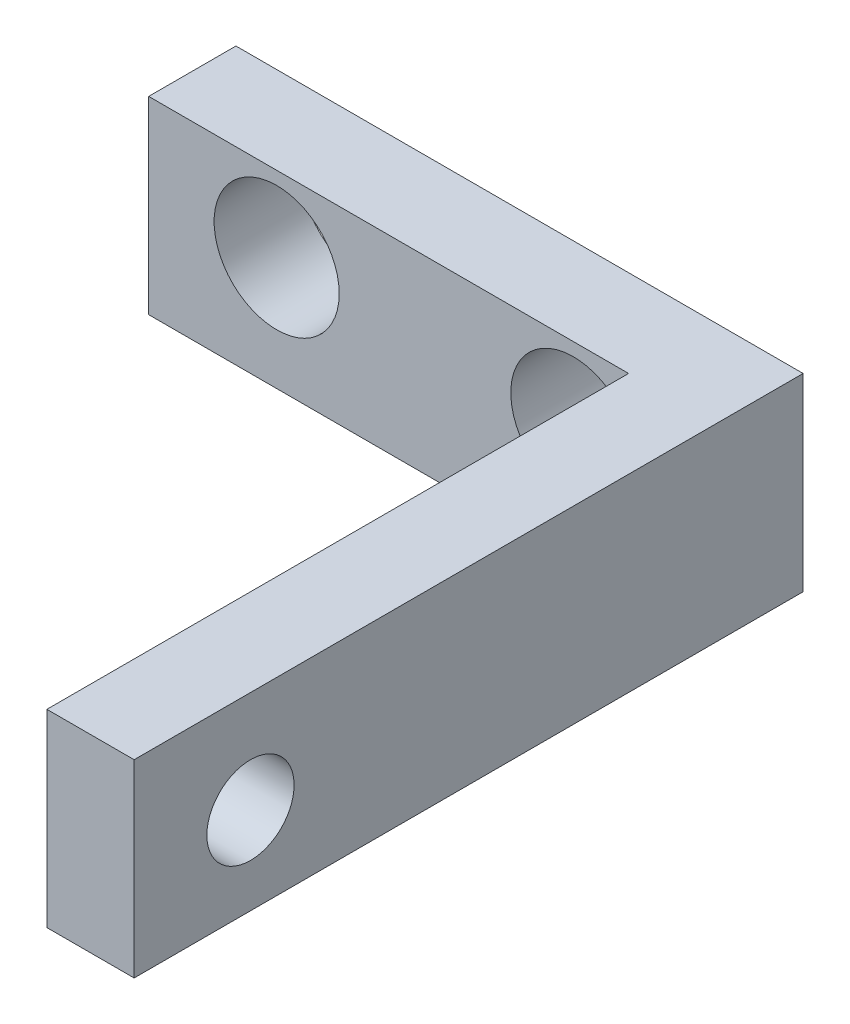
SolidWorks part; units mm, degrees
ref_plane "Front Plane" through (0, 0, 0) normal (0, 0, 1) x (1, 0, 0)
ref_plane "Top Plane" through (0, 0, 0) normal (0, 1, 0) x (1, 0, 0)
ref_plane "Right Plane" through (0, 0, 0) normal (1, 0, 0) x (0, 0, -1)
sketch "Sketch1" plane through (0, 0, 0) normal (0, 0, 1) x (1, 0, 0)
  line L0 (14.3846, -19.5704) -> (14.3846, -24.9359) construction
  line L1 (14.3846, -17.7588) -> (33.8846, -17.7588)
  line L2 (14.3846, -17.7588) -> (14.3846, -24.2588)
  line L3 (14.3846, -24.2588) -> (33.8846, -24.2588)
  line L4 (33.8846, -17.7588) -> (33.8846, -24.2588)
  line L5 (27.6846, -17.7588) -> (20.0846, -17.7588) construction
  line L11 (33.8846, -0.7588) -> (33.8846, 91.2412) construction
extrude "Boss-Extrude1" add sketch "Sketch1" along normal blind 3
sketch "Sketch2" plane through (0, 0, 3) normal (0, 0, 1) x (1, 0, 0)
  line L0 (14.3846, -24.2588) -> (33.8846, -24.2588) construction
  line L1 (33.8846, -17.7588) -> (30.8846, -17.7588)
  line L2 (33.8846, -17.7588) -> (33.8846, -24.2588)
  line L3 (33.8846, -24.2588) -> (30.8846, -24.2588)
  line L4 (30.8846, -17.7588) -> (30.8846, -24.2588)
  dimension "D1" = 3
extrude "Boss-Extrude2" add sketch "Sketch2" along normal blind 20
sketch "Sketch3" plane through (30.8846, 0, 0) normal (-1, 0, 0) x (0, 0, 1)
  line L0 (23, -17.7588) -> (23, -24.2588) construction
  line L1 (23, -17.7588) -> (3, -17.7588) construction
  circle A0 centre (19, -21.2588) radius 1.5
  dimension "D1" = 3
  dimension "D3" = 4
  dimension "D4" = 3.5
extrude "Cut-Extrude1" cut sketch "Sketch3" against normal blind 10
sketch "Sketch4" plane through (0, 0, 3) normal (0, 0, 1) x (1, 0, 0)
  line L0 (30.8846, -17.7588) -> (14.3846, -17.7588) construction
  circle A0 centre (28.9846, -20.3588) radius 2.15
  circle A1 centre (18.7846, -20.3588) radius 2.15
  dimension "D3" = 4.3
  dimension "D4" = 4.3
  dimension "D1" = 1.9
  dimension "D2" = 2.6
  dimension "D5" = 10.2
extrude "Cut-Extrude2" cut sketch "Sketch4" against normal blind 10 and the other way blind 10
sketch "Sketch5" plane through (30.8846, 0, 0) normal (-1, 0, 0) x (0, 0, 1)
  line L0 (3, -17.7588) -> (3, -19.3526) construction
  line L1 (3, -18.5557) -> (13.8814, -18.5557)
  line L2 (3, -18.5557) -> (3, -23.0503)
  line L3 (3, -23.0503) -> (13.8814, -23.0503)
  line L4 (13.8814, -18.5557) -> (13.8814, -23.0503)
extrude "Cut-Extrude3" cut sketch "Sketch5" against normal blind 1
